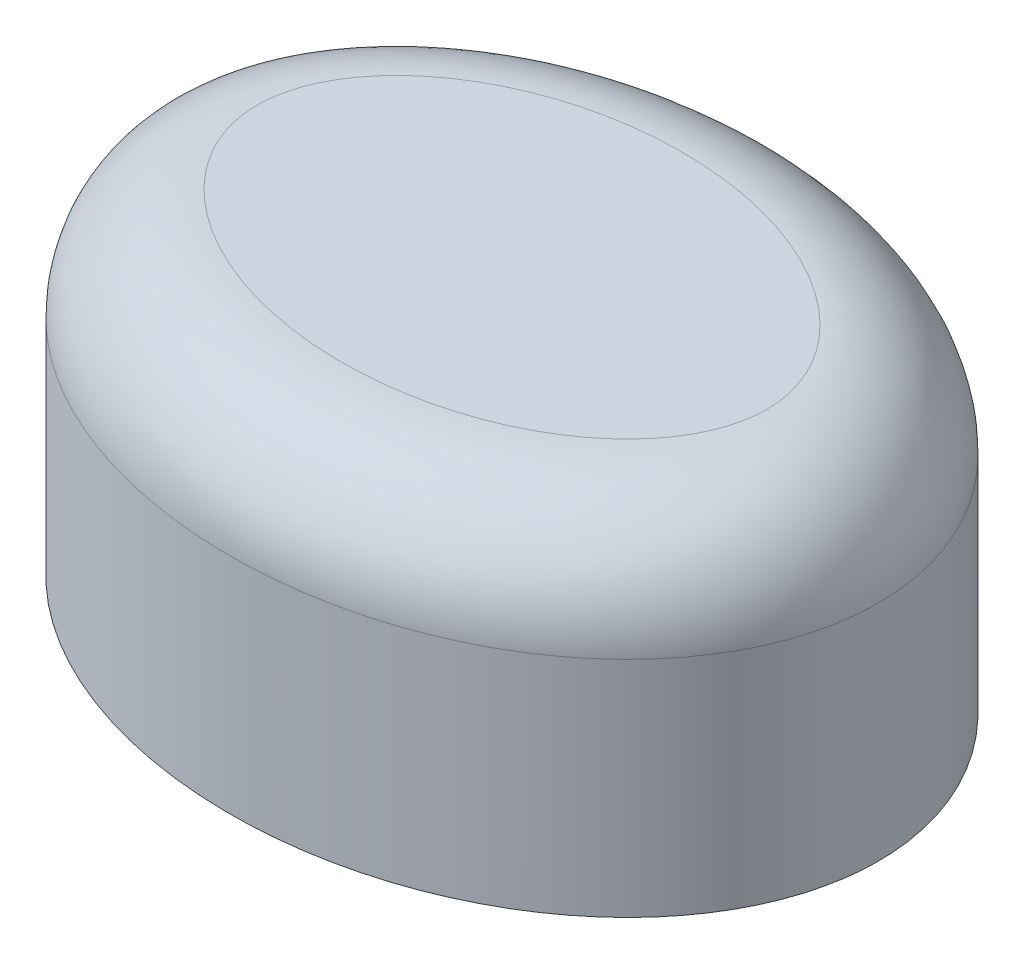
SolidWorks part; units mm, degrees
ref_plane "Ebene vorne" through (0, 0, 0) normal (0, 0, 1) x (1, 0, 0)
ref_plane "Ebene oben" through (0, 0, 0) normal (0, 1, 0) x (1, 0, 0)
ref_plane "Ebene rechts" through (0, 0, 0) normal (1, 0, 0) x (0, 0, -1)
sketch "Skizze4" plane through (0, 0, 0) normal (0, 1, 0) x (1, 0, 0)
  ellipse E0 centre (0, 0) end of major axis (33.1792, -0.9859) minor radius 25.7531
  point P1 (0.7649, 25.7418)
extrude "Aufsatz-Linear austragen2" add sketch "Skizze4" along normal blind 30
fillet "Verrundung4" radius 10 1 edges at (33.1792, 30, 0.9859)
